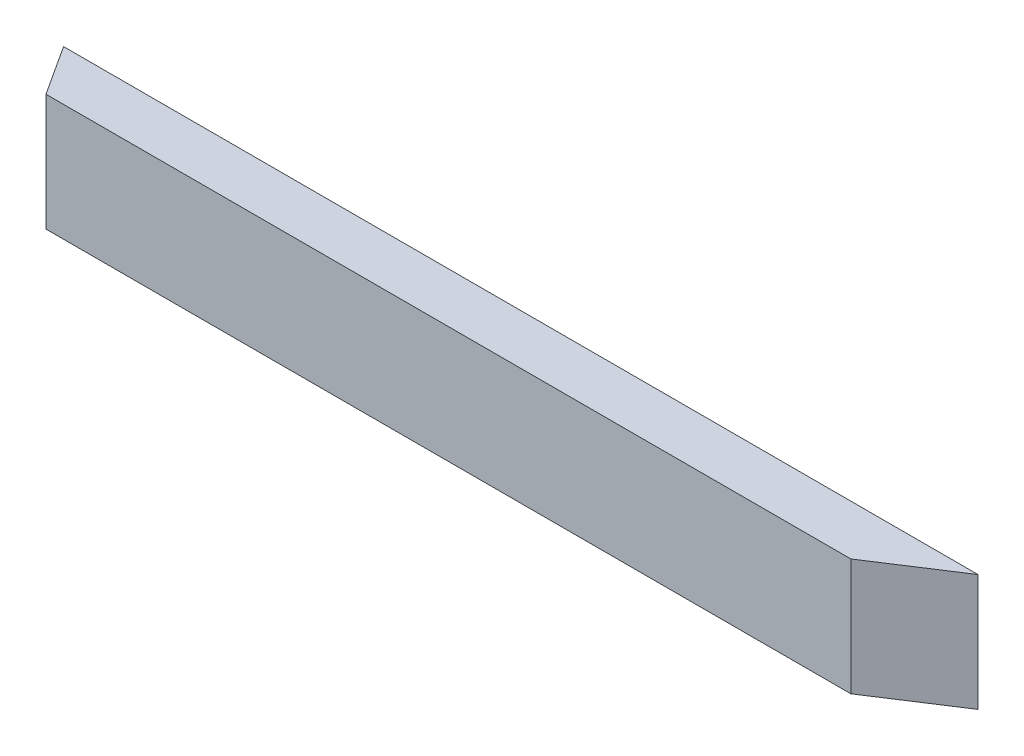
SolidWorks part; units mm, degrees
ref_plane "Front Plane" through (0, 0, 0) normal (0, 0, 1) x (1, 0, 0)
ref_plane "Top Plane" through (0, 0, 0) normal (0, 1, 0) x (1, 0, 0)
ref_plane "Right Plane" through (0, 0, 0) normal (1, 0, 0) x (0, 0, -1)
sketch "Sketch1" plane through (0, 0, 0) normal (0, 1, 0) x (1, 0, 0)
  line L0 (0, 0) -> (695.96, 0)
  line L1 (695.96, 0) -> (637.2911, -38.1)
  line L3 (24.7424, -38.1) -> (0, 0)
  line L4 (637.2911, -38.1) -> (24.7424, -38.1)
  point P3 (30.764, -43.3705)
  dimension "D1" = 695.96
  dimension "D2" = 57
  dimension "D3" = 33
  dimension "D4" = 38.1
extrude "Boss-Extrude1" add sketch "Sketch1" along normal blind 88.9
